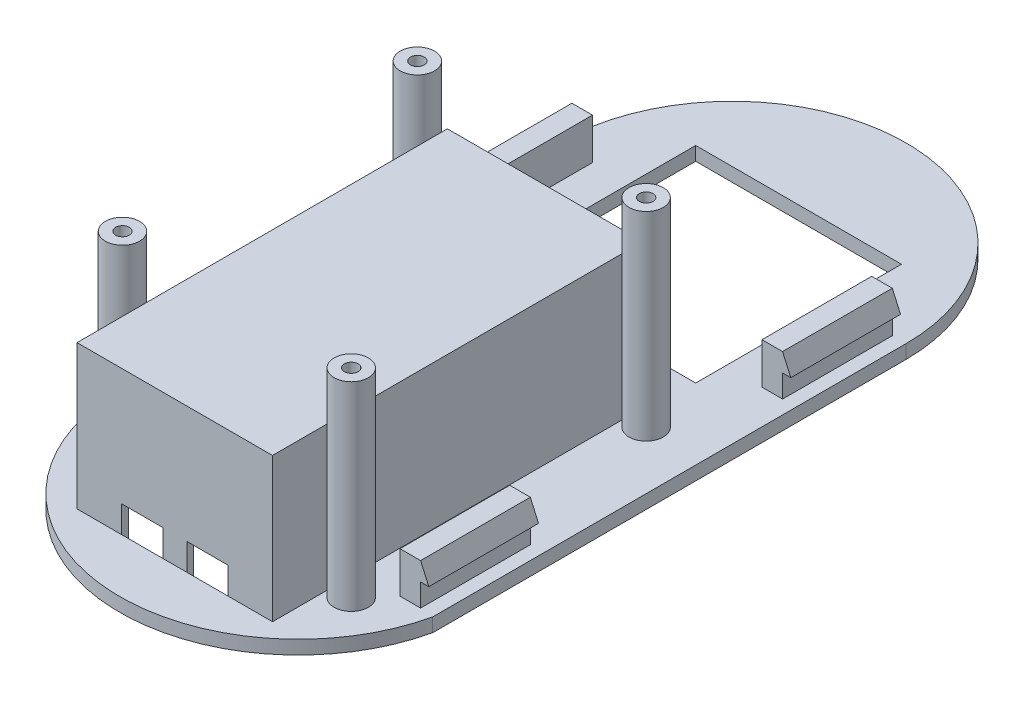
SolidWorks part; units mm, degrees
ref_plane "Alzado" through (0, 0, 0) normal (0, 0, 1) x (1, 0, 0)
ref_plane "Planta" through (0, 0, 0) normal (0, 1, 0) x (1, 0, 0)
ref_plane "Vista lateral" through (0, 0, 0) normal (1, 0, 0) x (0, 0, -1)
sketch "Croquis1" plane through (0, 0, 0) normal (0, 1, 0) x (1, 0, 0)
  line L13 (-64.418, -3.8768) -> (-37.918, -3.8768) construction
  line L14 (-64.418, -3.8768) -> (-64.418, -56.8768) construction
  line L15 (-64.418, -56.8768) -> (-37.918, -56.8768) construction
  line L16 (-37.918, -3.8768) -> (-37.918, -56.8768) construction
  line L18 (-70.668, 29.7663) -> (-31.668, 29.7663) construction
  line L19 (-31.668, 29.7663) -> (-31.668, -42.6244) construction
  line L20 (-31.668, -42.6244) -> (-70.668, -42.6244) construction
  line L21 (-70.668, -42.6244) -> (-70.668, 29.7663) construction
  line L22 (-76.5277, 21.978) -> (-25.8083, 21.978) construction
  line L23 (-28.3083, -46.7452) -> (-28.3083, 21.978)
  line L24 (-66.168, 27.1087) -> (-36.168, 27.1087) construction
  line L25 (-74.0277, -46.8931) -> (-74.0277, 21.978)
  line L27 (-66.168, 27.1087) -> (-66.168, -2.8913) construction
  line L28 (-66.168, -2.8913) -> (-36.168, -2.8913) construction
  line L29 (-76.5277, -47.1889) -> (-76.5277, 21.978)
  line L30 (-25.8083, -47.0331) -> (-25.8083, 21.978)
  line L31 (-36.168, 27.1087) -> (-36.168, -2.8913) construction
  arc A11 (-76.5277, -47.1889) -> (-25.8083, -47.0331) centre (-51.186, -41.2624) ccw
  arc A12 (-74.0277, 21.978) -> (-28.3083, 21.978) centre (-51.168, 21.978) cw
  circle A13 centre (-51.168, 21.978) radius 18 construction
  circle A14 centre (-51.168, -12.9154) radius 6
  arc A15 (-74.0277, -46.8931) -> (-28.3083, -46.7452) centre (-51.186, -41.2624) ccw
  arc A16 (-76.5277, 21.978) -> (-25.8083, 21.978) centre (-51.168, 21.978) cw
  circle A21 centre (-51.168, 21.978) radius 16
extrude "Saliente-Extruir1" add sketch "Croquis1" along normal blind 2 contours L30 A16 L29 A11
sketch "Croquis2" plane through (0, 2, 0) normal (0, 1, 0) x (1, 0, 0)
  line L6 (-27.8083, -46.804) -> (-27.8083, 21.978)
  line L7 (-74.5277, 21.978) -> (-74.5277, -46.9535)
  line L8 (-27.8083, -46.804) -> (-27.8083, 21.978)
  line L9 (-74.5277, 21.978) -> (-74.5277, -46.9535)
  arc A6 (-74.5277, -46.9535) -> (-27.8083, -46.804) centre (-51.186, -41.2624) ccw
  arc A7 (-27.8083, 21.978) -> (-74.5277, 21.978) centre (-51.168, 21.978) ccw
  arc A8 (-74.5277, -46.9535) -> (-27.8083, -46.804) centre (-51.186, -41.2624) ccw
  arc A9 (-27.8083, 21.978) -> (-74.5277, 21.978) centre (-51.168, 21.978) ccw
  dimension "D1" = 2
sketch "Croquis3" plane through (0, 2, 0) normal (0, 1, 0) x (1, 0, 0)
  line L1 (-65.3749, -5.3284) -> (-36.8749, -5.3284)
  line L2 (-65.3749, -5.3284) -> (-65.3749, -59.3284)
  line L3 (-65.3749, -59.3284) -> (-36.8749, -59.3284)
  line L4 (-36.8749, -5.3284) -> (-36.8749, -59.3284)
extrude "Saliente-Extruir2" add sketch "Croquis3" along normal blind 21 contours L1 L4 L3 L2
sketch "Croquis7" plane through (0, 23, 0) normal (0, 1, 0) x (1, 0, 0)
  line L8 (-64.3749, -6.3284) -> (-64.3749, -58.3284)
  line L9 (-64.3749, -58.3284) -> (-37.8749, -58.3284)
  line L10 (-37.8749, -58.3284) -> (-37.8749, -6.3284)
  line L11 (-37.8749, -6.3284) -> (-64.3749, -6.3284)
  line L12 (-64.3749, -6.3284) -> (-64.3749, -58.3284)
  line L13 (-64.3749, -58.3284) -> (-37.8749, -58.3284)
  line L14 (-37.8749, -58.3284) -> (-37.8749, -6.3284)
  line L15 (-37.8749, -6.3284) -> (-64.3749, -6.3284)
  dimension "D1" = 1
extrude "Cortar-Extruir2" cut sketch "Croquis7" against normal blind 61 and the other way blind 21 from surface at -23 contours L15 L12 L13 L14 starting at face at (-51.1525, 0, 11.2708)
sketch "Croquis10" plane through (0, 0, 5.3284) normal (0, 0, -1) x (-1, 0, 0)
  line L0 (65.3749, 2) -> (36.8749, 2) construction
  line L1 (41.8749, 2) -> (60.3749, 2)
  line L2 (41.8749, 2) -> (41.8749, 15)
  line L3 (41.8749, 15) -> (60.3749, 15)
  line L4 (60.3749, 2) -> (60.3749, 15)
other "Alinear grupo1"
extrude "Cortar-Extruir3" cut sketch "Croquis10" against normal blind 10
sketch "Croquis11" plane through (0, 0, 0) normal (0, -1, 0) x (1, 0, 0)
  line L10 (-65.3749, 5.3284) -> (-36.8749, 5.3284)
  line L11 (-36.8749, 5.3284) -> (-36.8749, 59.3284)
  line L12 (-36.8749, 59.3284) -> (-65.3749, 59.3284)
  line L13 (-65.3749, 59.3284) -> (-65.3749, 5.3284)
  line L14 (-65.3749, 5.3284) -> (-36.8749, 5.3284)
  line L15 (-36.8749, 5.3284) -> (-36.8749, 59.3284)
  line L16 (-36.8749, 59.3284) -> (-65.3749, 59.3284)
  line L17 (-65.3749, 59.3284) -> (-65.3749, 5.3284)
  dimension "D1" = 1
extrude "Cortar-Extruir4" cut sketch "Croquis11" against normal blind 0.9 contours L17 L14 L15 L16
sketch "Croquis12" plane through (0, 2, 0) normal (0, 1, 0) x (1, 0, 0)
  line L0 (-51.168, 47.3377) -> (-51.168, -3.5297)
  line L2 (-66.168, 31.6716) -> (-36.168, 31.6716)
  line L3 (-66.168, 31.6716) -> (-66.168, 1.6716)
  line L4 (-66.168, 1.6716) -> (-36.168, 1.6716)
  line L5 (-36.168, 31.6716) -> (-36.168, 1.6716)
  arc A0 (-25.8083, 21.978) -> (-76.5277, 21.978) centre (-51.168, 21.978) ccw construction
extrude "Cortar-Extruir6" cut sketch "Croquis12" against normal blind 20.6 contours L2 L5 L4 L3
sketch "Croquis13" plane through (0, 2, 0) normal (0, 1, 0) x (1, 0, 0)
  line L1 (-27.8083, -46.804) -> (-30.8083, -46.804)
  line L2 (-27.8083, -46.804) -> (-27.8083, -30.804)
  line L3 (-27.8083, -30.804) -> (-30.8083, -30.804)
  line L4 (-30.8083, -46.804) -> (-30.8083, -30.804)
  line L5 (-74.5277, -46.9535) -> (-71.5277, -46.9535)
  line L6 (-74.5277, -46.9535) -> (-74.5277, -30.9535)
  line L7 (-74.5277, -30.9535) -> (-71.5277, -30.9535)
  line L8 (-71.5277, -46.9535) -> (-71.5277, -30.9535)
  line L9 (-74.5277, 21.978) -> (-71.5277, 21.978)
  line L10 (-74.5277, 21.978) -> (-74.5277, 5.978)
  line L11 (-74.5277, 5.978) -> (-71.5277, 5.978)
  line L12 (-71.5277, 21.978) -> (-71.5277, 5.978)
  line L13 (-27.8083, 21.978) -> (-30.8083, 21.978)
  line L14 (-27.8083, 21.978) -> (-27.8083, 5.978)
  line L15 (-27.8083, 5.978) -> (-30.8083, 5.978)
  line L16 (-30.8083, 21.978) -> (-30.8083, 5.978)
extrude "Saliente-Extruir5" add sketch "Croquis13" along normal blind 6 contours L8 L7 L6 L5 | L12 L11 L10 L9 | L4 L3 L2 L1 | L16 L15 L14 L13
sketch "Croquis18" plane through (0, 0, 46.804) normal (0, 0, 1) x (1, 0, 0)
  line L0 (-27.8083, 8) -> (-27.8083, 5.3)
  line L1 (-27.8083, 8) -> (-27.8083, 2) construction
  line L2 (-27.8083, 5.3) -> (-26.6083, 5.3)
  line L3 (-26.6083, 5.3) -> (-27.8083, 8)
extrude "Saliente-Extruir9" add sketch "Croquis18" against normal blind 16 contours L3 L0 L2
sketch "Croquis21" plane through (0, 0, 46.9535) normal (0, 0, 1) x (1, 0, 0)
  line L0 (-74.5277, 8) -> (-74.5277, 5.3)
  line L1 (-74.5277, 8) -> (-74.5277, 2) construction
  line L2 (-74.5277, 5.3) -> (-75.7277, 5.3)
  line L3 (-75.7277, 5.3) -> (-74.5277, 8)
extrude "Saliente-Extruir10" add sketch "Croquis21" against normal blind 16 contours L3 L0 L2
sketch "Croquis22" plane through (0, 0, -21.978) normal (0, 0, -1) x (-1, 0, 0)
  line L0 (27.8083, 8) -> (27.8083, 5.3)
  line L1 (27.8083, 5.3) -> (26.6083, 5.3)
  line L2 (26.6083, 5.3) -> (27.8083, 8)
extrude "Saliente-Extruir11" add sketch "Croquis22" against normal blind 16 contours L2 L0 L1
sketch "Croquis23" plane through (0, 0, -21.978) normal (0, 0, -1) x (-1, 0, 0)
  line L0 (74.5277, 8) -> (74.5277, 5.3)
  line L1 (74.5277, 5.3) -> (75.7277, 5.3)
  line L2 (75.7277, 5.3) -> (74.5277, 8)
extrude "Saliente-Extruir12" add sketch "Croquis23" against normal blind 16 contours L2 L0 L1
sketch "Croquis25" plane through (0, 0, 0) normal (0, -1, 0) x (1, 0, 0)
  line L0 (-65.3749, 5.3284) -> (-36.8749, 5.3284) construction
  line L1 (-51.1249, 5.3284) -> (-55.6249, 5.3284)
  line L2 (-51.1249, 5.3284) -> (-51.1249, 3.8784)
  line L3 (-51.1249, 3.8784) -> (-55.6249, 3.8784)
  line L4 (-55.6249, 5.3284) -> (-55.6249, 3.8784)
extrude "Cortar-Extruir7" cut sketch "Croquis25" against normal blind 0.9
sketch "Croquis26" plane through (0, 0, 58.3284) normal (0, 0, -1) x (-1, 0, 0)
  line L0 (37.8749, 0.9) -> (64.3749, 0.9) construction
  line L1 (58.8749, 0.9) -> (52.8749, 0.9)
  line L2 (58.8749, 0.9) -> (58.8749, 5.9)
  line L3 (58.8749, 5.9) -> (52.8749, 5.9)
  line L4 (52.8749, 0.9) -> (52.8749, 5.9)
  line L6 (43.3749, 0.9) -> (49.3749, 0.9)
  line L7 (43.3749, 0.9) -> (43.3749, 5.9)
  line L8 (43.3749, 5.9) -> (49.3749, 5.9)
  line L9 (49.3749, 0.9) -> (49.3749, 5.9)
extrude "Cortar-Extruir9" cut sketch "Croquis26" along normal blind 0.9 and the other way blind 1
sketch "Croquis32" plane through (0, 2, 0) normal (0, 1, 0) x (1, 0, 0)
  line L0 (-30.8083, -46.804) -> (-30.8083, -49.804)
  line L1 (-71.5277, -46.9535) -> (-71.5277, -49.9535)
  line L2 (-68.1277, -49.9535) -> (-68.1277, -6.9535)
  line L3 (-34.2083, -50.5155) -> (-34.2083, -7.5155)
  circle A0 centre (-68.1277, -49.9535) radius 2.5
  circle A1 centre (-68.1277, -6.9535) radius 2.5
  circle A2 centre (-34.2083, -50.5155) radius 2.5
  circle A3 centre (-34.2083, -7.5155) radius 2.5
  dimension "D2" = 3
  dimension "D3" = 5
  dimension "D4" = 3
  dimension "D6" = 3.4
  dimension "D1" = 43
  dimension "D5" = 3.4
  dimension "D7" = 43
extrude "Saliente-Extruir13" add sketch "Croquis32" along normal blind 29 contours A1 | A0 | A2 | A3
sketch "Croquis36" plane through (0, 31, 0) normal (0, 1, 0) x (1, 0, 0)
  circle A0 centre (-68.1277, -6.9535) radius 1
extrude "Cortar-Extruir10" cut sketch "Croquis36" against normal blind 4.5 contours A0
sketch "Croquis37" plane through (0, 31, 0) normal (0, 1, 0) x (1, 0, 0)
  circle A0 centre (-34.2083, -7.5155) radius 1
sketch "Croquis38" plane through (0, 31, 0) normal (0, 1, 0) x (1, 0, 0)
  circle A0 centre (-34.2083, -50.5155) radius 1
sketch "Croquis39" plane through (0, 31, 0) normal (0, 1, 0) x (1, 0, 0)
  circle A0 centre (-68.1277, -49.9535) radius 1
extrude "Cortar-Extruir11" cut sketch "Croquis39" against normal blind 4.5 contours A0
extrude "Cortar-Extruir12" cut sketch "Croquis38" against normal blind 4.5 contours A0
extrude "Cortar-Extruir13" cut sketch "Croquis37" against normal blind 4.5 contours A0
